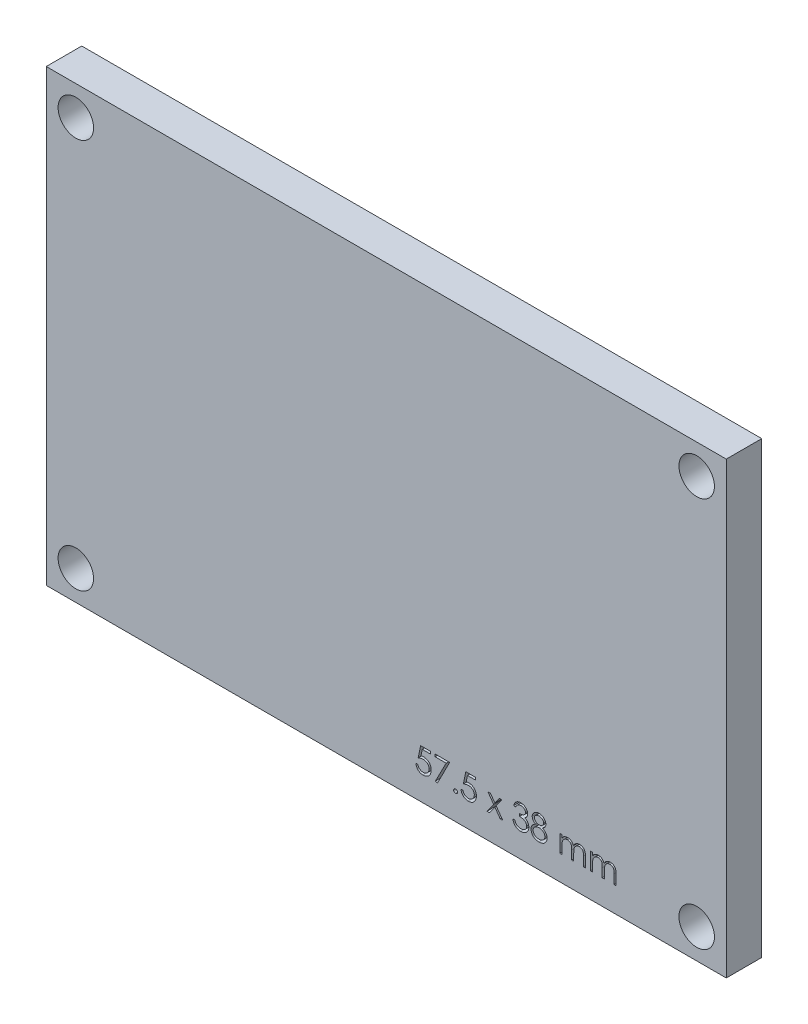
SolidWorks part; units mm, degrees
ref_plane "Front Plane" through (0, 0, 0) normal (0, 0, 1) x (1, 0, 0)
ref_plane "Top Plane" through (0, 0, 0) normal (0, 1, 0) x (1, 0, 0)
ref_plane "Right Plane" through (0, 0, 0) normal (1, 0, 0) x (0, 0, -1)
sketch "Sketch1" plane through (0, 0, 0) normal (0, 0, 1) x (1, 0, 0)
  line L1 (-28.75, 19) -> (28.75, 19)
  line L2 (-28.75, 19) -> (-28.75, -19)
  line L3 (-28.75, -19) -> (28.75, -19)
  line L4 (28.75, 19) -> (28.75, -19)
  line L5 (-28.75, 19) -> (28.75, -19) construction
  line L6 (-28.75, -19) -> (28.75, 19) construction
  dimension "D1" = 38
  dimension "D2" = 57.5
  dimension "D3" = 19
  dimension "D4" = 28.75
extrude "Boss-Extrude1" add sketch "Sketch1" along normal blind 3 contours L1 L4 L3 L2
sketch "Sketch2" plane through (0, 0, 3) normal (0, 0, 1) x (1, 0, 0)
  line L0 (1.65, 0) -> (-1.65, 0) construction
  line L3 (28.75, 19) -> (28.75, -19) construction
  line L6 (-28.75, -19) -> (28.75, -19) construction
  line L7 (-28.75, 19) -> (28.75, 19) construction
  line L9 (-28.75, 19) -> (-28.75, -19) construction
  circle A0 centre (-26.25, 16.5) radius 1.5
  circle A1 centre (-26.25, -16.5) radius 1.5
  circle A4 centre (26.25, 16.5) radius 1.5
  circle A5 centre (26.25, -16.5) radius 1.5
  dimension "D1" = 3
  dimension "D2" = 1
  dimension "D3" = 1
  dimension "D4" = 3
  dimension "D5" = 3
  dimension "D6" = 1
  dimension "D7" = 1
  dimension "D8" = 1
  dimension "D9" = 1
extrude "Cut-Extrude1" cut sketch "Sketch2" against normal through all both and the other way through all
sketch "Sketch4" plane through (0, 0, 3) normal (0, 0, 1) x (1, 0, 0)
  text T0 "57.5 x 38 mm\r\n" font "Century Gothic" height 2
extrude "Cut-Extrude2" cut sketch "Sketch4" against normal blind 1
